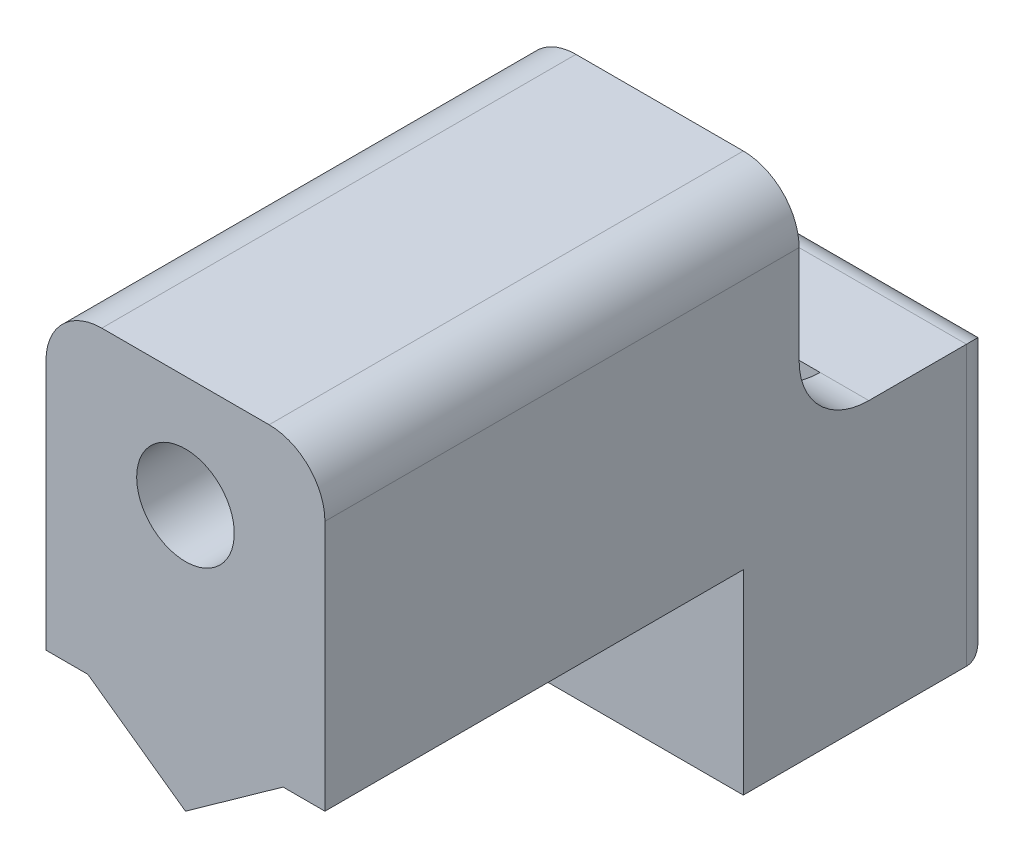
SolidWorks part; units mm, degrees
ref_plane "Спереди" through (0, 0, 0) normal (0, 0, 1) x (1, 0, 0)
ref_plane "Сверху" through (0, 0, 0) normal (0, 1, 0) x (1, 0, 0)
ref_plane "Справа" through (0, 0, 0) normal (1, 0, 0) x (0, 0, -1)
sketch "Эскиз3" plane through (0, 0, 0) normal (0, 0, 1) x (1, 0, 0)
  line L0 (0, -6.75) -> (-3.5, -4.25)
  line L1 (-3.5, -4.25) -> (-5, -4.25)
  line L2 (-5, -4.25) -> (-5, 4.75)
  line L3 (-5, 4.75) -> (-5, 6.75)
  line L4 (-5, 6.75) -> (5, 6.75)
  line L5 (5, 6.75) -> (5, -4.25)
  line L6 (5, -4.25) -> (3.5, -4.25)
  line L7 (3.5, -4.25) -> (0, -6.75)
extrude "Бобышка-Вытянуть1" add sketch "Эскиз3" along normal blind 7
sketch "Эскиз6" plane through (0, 0, 0) normal (0, 0, -1) x (-1, 0, 0)
  line L0 (0, -6.75) -> (0, 2.75)
  circle A0 centre (0, 2.75) radius 1.5
  dimension "D2" = 3
  dimension "D1" = 9.5
extrude "Вырез-Вытянуть1" cut sketch "Эскиз6" against normal through all
sketch "Эскиз7" plane through (0, 0, 0) normal (0, 0, -1) x (-1, 0, 0)
  line L0 (-5, 6.75) -> (5, 6.75) construction
  line L1 (1.5877, 0) -> (3.1754, 2.75)
  line L2 (3.1754, 2.75) -> (1.5877, 5.5)
  line L3 (1.5877, 5.5) -> (-1.5877, 5.5)
  line L4 (-1.5877, 5.5) -> (-3.1754, 2.75)
  line L5 (-3.1754, 2.75) -> (-1.5877, 0)
  line L6 (-1.5877, 0) -> (1.5877, 0)
  circle A0 centre (0, 2.75) radius 2.75 construction
  dimension "D1" = 5.5
extrude "Вырез-Вытянуть2" cut sketch "Эскиз7" against normal blind 3
sketch "Эскиз8" plane through (0, 0, 0) normal (0, 0, -1) x (-1, 0, 0)
  line L0 (5, 6.75) -> (5, -4.25) construction
  line L1 (-5, -4.25) -> (5, -4.25)
  line L2 (-5, -4.25) -> (-5, -8.75)
  line L3 (-5, -8.75) -> (5, -8.75)
  line L4 (5, -4.25) -> (5, -8.75)
  line L5 (-5, -4.25) -> (5, -4.25)
  line L6 (-5, -4.25) -> (-5, -1.25)
  line L7 (-5, -1.25) -> (5, -1.25)
  line L8 (5, -4.25) -> (5, -1.25)
  line M11 (3.5, -4.25) -> (5, -4.25)
  line M12 (5, -4.25) -> (5, 6.75)
  line M14 (-5, 6.75) -> (-5, -4.25)
  line M15 (-5, -4.25) -> (-3.5, -4.25)
  dimension "D1" = 4.5
  dimension "D2" = 3
extrude "Бобышка-Вытянуть3" add sketch "Эскиз8" along normal blind 7 contours L7 L1 M14 M15 M11 M12
sketch "Эскиз10" plane through (0, -4.25, 0) normal (0, -1, 0) x (1, 0, 0)
  line L0 (-5, 7) -> (-5, -7) construction
  line L1 (5, -7) -> (-5, -7)
  line L2 (5, -7) -> (5, 0)
  line L3 (5, 0) -> (-5, 0)
  line L4 (-5, -7) -> (-5, 0)
extrude "Бобышка-Вытянуть4" add sketch "Эскиз10" along normal blind 7
sketch "Эскиз12" plane through (0, 0, -7) normal (0, 0, -1) x (-1, 0, 0)
  line L0 (0, -11.25) -> (0, -1.25)
  line L1 (5, -11.25) -> (-5, -11.25) construction
  line L2 (-5, -1.25) -> (5, -1.25) construction
  line L3 (-5, -6.25) -> (5, -6.25)
  line L4 (-5, -1.25) -> (-5, -11.25) construction
  line L5 (5, -11.25) -> (5, -1.25) construction
  line L6 (0, -6.25) -> (0, -4.9353)
  line L7 (0, -4.9353) -> (-3.25, -4.9353)
  line L8 (-3.25, -4.9353) -> (-3.25, -7.4353)
  line L9 (-3.25, -7.4353) -> (3.25, -7.4353)
  line L10 (3.25, -7.4353) -> (3.25, -4.9353)
  line L11 (3.25, -4.9353) -> (0, -4.9353)
  line L12 (0, -4.9353) -> (0, -4.8193)
  dimension "D1" = 6.5
  dimension "D2" = 2.5
extrude "Вырез-Вытянуть3" cut sketch "Эскиз12" against normal blind 7 contours L7 L8 L3 L0 | L10 L11 L0 L3 | L9 L10 L3 L0 | L8 L9 L0 L3
sketch "Эскиз13" plane through (0, -1.25, 0) normal (0, 1, 0) x (1, 0, 0)
  line L0 (0, 0) -> (3.25, 0)
  line L1 (5, 0) -> (-5, 0) construction
  line L2 (3.25, 0) -> (3.25, 2.5)
  line L3 (3.25, 2.5) -> (-3.25, 2.5)
  line L4 (-3.25, 2.5) -> (-3.25, 0)
  line L5 (-3.25, 0) -> (0, 0)
  dimension "D1" = 6.5
  dimension "D2" = 2.5
extrude "Вырез-Вытянуть4" cut sketch "Эскиз13" against normal blind 6.2
fillet "Скругление1" radius 2.5 2 edges
fillet "Скругление2" radius 1 4 edges at (0, -11.25, -7) (5, -6.25, -7) (-5, -6.25, -7) (0, -1.25, -7)
fillet "Скругление4" radius 2 2 edges at (5, 6.75, 3.5) (-5, 6.75, 3.5)
sketch "Эскиз14" plane through (0, 0, 7) normal (0, 0, 1) x (1, 0, 0)
  line L0 (-5, -4.25) -> (-5, 4.75)
  line L1 (-5, 4.75) -> (-5, -4.25)
  line L2 (-3.5, -4.25) -> (0, -6.75)
  line L3 (0, -6.75) -> (3.375, -4.3393)
  line L4 (3.25, -4.4286) -> (3.5, -4.25) construction
  line L5 (3.375, -4.3393) -> (5, -4.25)
  line L6 (5, -4.25) -> (5, 4.75)
  line L7 (-3, 6.75) -> (3, 6.75)
  circle A0 centre (0, 2.75) radius 1.5
  arc A1 (-5, 4.75) -> (-3, 6.75) centre (-3, 4.75) cw
  arc A2 (3, 6.75) -> (5, 4.75) centre (3, 4.75) cw
  circle M1 centre (0, 2.75) radius 1.5
  line M2 (5, -4.25) -> (5, 4.75)
  arc M3 (5, 4.75) -> (3, 6.75) centre (3, 4.75) ccw
  line M4 (3, 6.75) -> (-3, 6.75)
  arc M5 (-3, 6.75) -> (-5, 4.75) centre (-3, 4.75) ccw
  line M6 (-5, 4.75) -> (-5, -4.25)
  line M7 (-5, -4.25) -> (-3.5, -4.25)
  line M8 (-3.5, -4.25) -> (0, -6.75)
  line M9 (0, -6.75) -> (3.5, -4.25)
  line M10 (3.5, -4.25) -> (5, -4.25)
extrude "Бобышка-Вытянуть5" add sketch "Эскиз14" along normal blind 10 contours M10 M2 M3 M4 M5 M6 M7 M8 M9 M1
sketch "Эскиз15" plane through (0, 0, 0) normal (0, 0, 1) x (1, 0, 0)
  line L1 (-5, -11.25) -> (5, -11.25)
  line L2 (-5, -11.25) -> (-5, -4.25)
  line L3 (-5, -4.25) -> (5, -4.25)
  line L4 (5, -11.25) -> (5, -4.25)
extrude "Бобышка-Вытянуть6" add sketch "Эскиз15" along normal blind 2
sketch "Эскиз17" plane through (0, 0, 0) normal (0, 0, -1) x (-1, 0, 0)
  line L1 (1.5877, 0) -> (3.1754, 2.75)
  line L2 (3.1754, 2.75) -> (1.5877, 5.5)
  line L3 (1.5877, 5.5) -> (-1.5877, 5.5)
  line L4 (-1.5877, 5.5) -> (-3.1754, 2.75)
  line L5 (-3.1754, 2.75) -> (-1.5877, 0)
  line L6 (-1.5877, 0) -> (1.5877, 0)
  circle A0 centre (0, 2.75) radius 2.75 construction
extrude "Вырез-Вытянуть5" cut sketch "Эскиз17" against normal blind 10
sketch "Эскиз18" plane through (0, 0, 0) normal (0, 0, -1) x (-1, 0, 0)
  line L1 (1.6454, -0.1) -> (3.2909, 2.75)
  line L2 (3.2909, 2.75) -> (1.6454, 5.6)
  line L3 (1.6454, 5.6) -> (-1.6454, 5.6)
  line L4 (-1.6454, 5.6) -> (-3.2909, 2.75)
  line L5 (-3.2909, 2.75) -> (-1.6454, -0.1)
  line L6 (-1.6454, -0.1) -> (1.6454, -0.1)
  circle A0 centre (0, 2.75) radius 2.85 construction
  dimension "D1" = 5.7
extrude "Вырез-Вытянуть6" cut sketch "Эскиз18" against normal blind 10
sketch "Эскиз19" plane through (0, 0, 10) normal (0, 0, -1) x (-1, 0, 0)
  circle A0 centre (0, 2.75) radius 1.75
  dimension "D1" = 3.5
extrude "Вырез-Вытянуть7" cut sketch "Эскиз19" against normal through all
